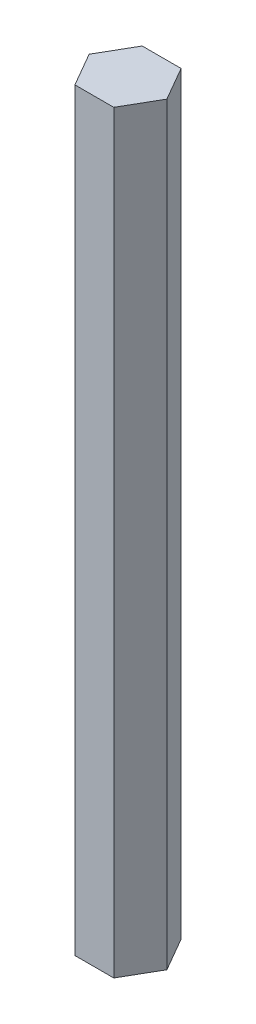
SolidWorks part; units mm, degrees
ref_plane "Front Plane" through (0, 0, 0) normal (0, 0, 1) x (1, 0, 0)
ref_plane "Top Plane" through (0, 0, 0) normal (0, 1, 0) x (1, 0, 0)
ref_plane "Right Plane" through (0, 0, 0) normal (1, 0, 0) x (0, 0, -1)
sketch "Sketch1" plane through (0, 0, 0) normal (0, 1, 0) x (1, 0, 0)
  line L1 (-7.3323, 0) -> (-3.6662, -6.35)
  line L2 (-3.6662, -6.35) -> (3.6662, -6.35)
  line L3 (3.6662, -6.35) -> (7.3323, 0)
  line L4 (7.3323, 0) -> (3.6662, 6.35)
  line L5 (3.6662, 6.35) -> (-3.6662, 6.35)
  line L6 (-3.6662, 6.35) -> (-7.3323, 0)
  circle A0 centre (0, 0) radius 6.35 construction
  dimension "D1" = 12.7
extrude "Boss-Extrude1" add sketch "Sketch1" along normal blind 142.24
